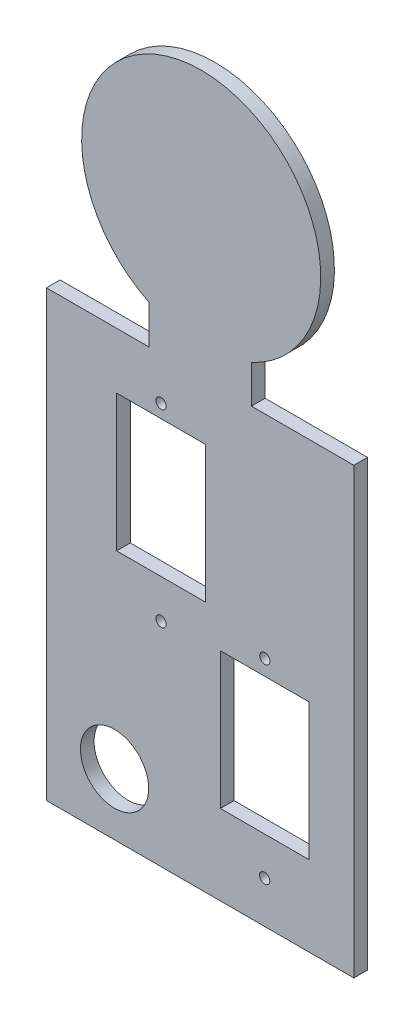
SolidWorks part; units mm, degrees
ref_plane "Front Plane" through (0, 0, 0) normal (0, 0, 1) x (1, 0, 0)
ref_plane "Top Plane" through (0, 0, 0) normal (0, 1, 0) x (1, 0, 0)
ref_plane "Right Plane" through (0, 0, 0) normal (1, 0, 0) x (0, 0, -1)
sketch "Sketch2" plane through (0, 0, 0) normal (0, 0, 1) x (1, 0, 0)
  line L0 (-7.6516, -15.7386) -> (-7.6516, -21.4191)
  line L1 (7.3484, -15.8824) -> (7.3484, -21.4191)
  line L2 (7.3484, -21.4191) -> (22.3484, -21.4191)
  line L3 (-22.6516, -21.4191) -> (-7.6516, -21.4191)
  line L4 (-22.6516, -21.4191) -> (-22.6516, -86.4191)
  line L5 (-22.6516, -86.4191) -> (22.3484, -86.4191)
  line L6 (22.3484, -21.4191) -> (22.3484, -86.4191)
  arc A0 (7.3484, -15.8824) -> (-7.6516, -15.7386) centre (0, 0) ccw
  dimension "D1" = 35
  dimension "D2" = 65
  dimension "D3" = 15
  dimension "D4" = 15
  dimension "D5" = 15
extrude "Boss-Extrude1" add sketch "Sketch2" along normal blind 2 contours L1 L2 L6 L5 L4 L3 L0 A0
sketch "Sketch3" plane through (0, 0, 2) normal (0, 0, 1) x (1, 0, 0)
  line L0 (2.8067, -54.6997) -> (15.8067, -54.6997)
  line L1 (-12.3746, -29.6313) -> (0.6254, -29.6313)
  line L2 (-12.3746, -29.6313) -> (-12.3746, -49.6313)
  line L3 (-12.3746, -49.6313) -> (0.6254, -49.6313)
  line L4 (0.6254, -29.6313) -> (0.6254, -49.6313)
  line L5 (2.8067, -54.6997) -> (2.8067, -74.6997)
  line L6 (2.8067, -74.6997) -> (15.8067, -74.6997)
  line L7 (15.8067, -54.6997) -> (15.8067, -74.6997)
  dimension "D1" = 13
  dimension "D2" = 20
extrude "Cut-Extrude1" cut sketch "Sketch3" against normal blind 11.5
sketch "Sketch4" plane through (0, 0, 2) normal (0, 0, 1) x (1, 0, 0)
  line L0 (-5.8746, -29.6313) -> (-5.8746, -28.7313) construction
  line L1 (0.6254, -29.6313) -> (-12.3746, -29.6313) construction
  line L2 (-5.8746, -49.6313) -> (-5.8746, -54.6313) construction
  line L3 (-12.3746, -49.6313) -> (0.6254, -49.6313) construction
  line L4 (9.3067, -54.6997) -> (9.3067, -53.1895) construction
  line L5 (15.8067, -54.6997) -> (2.8067, -54.6997) construction
  line L6 (9.3067, -74.6997) -> (9.2905, -80.2907) construction
  line L7 (2.8067, -74.6997) -> (15.8067, -74.6997) construction
  circle A0 centre (-5.8746, -27.6795) radius 0.75
  circle A1 centre (-5.8746, -55.3134) radius 0.75
  circle A2 centre (9.3182, -52.4319) radius 0.75
  circle A3 centre (9.2905, -80.2907) radius 0.75
  dimension "D1" = 1.5
  dimension "D2" = 1.5
  dimension "D3" = 0.9
  dimension "D5" = 1.5
  dimension "D6" = 1.5
  dimension "D4" = 5
extrude "Cut-Extrude2" cut sketch "Sketch4" against normal blind 4.5
sketch "Sketch5" plane through (0, 0, 2) normal (0, 0, 1) x (1, 0, 0)
  circle A0 centre (-12.6867, -77.4152) radius 5
  dimension "D1" = 10
extrude "Cut-Extrude3" cut sketch "Sketch5" against normal blind 10
